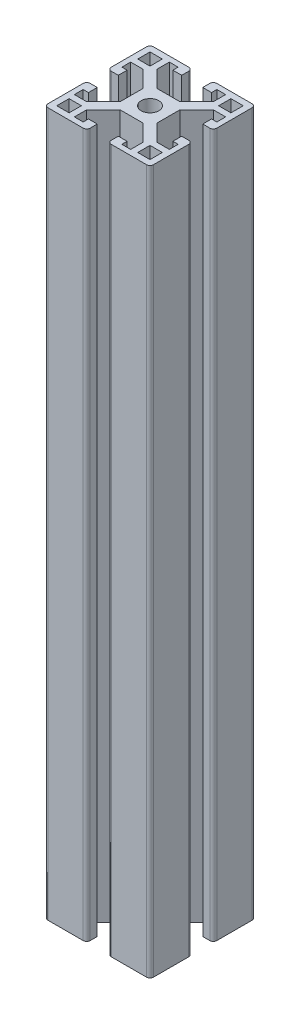
SolidWorks part; units mm, degrees
material "1060 Alloy"
ref_plane "Front Plane" through (0, 0, 0) normal (0, 0, 1) x (1, 0, 0)
ref_plane "Top Plane" through (0, 0, 0) normal (0, 1, 0) x (1, 0, 0)
ref_plane "Right Plane" through (0, 0, 0) normal (1, 0, 0) x (0, 0, -1)
sketch "Sketch1" plane through (0, 0, 0) normal (0, 1, 0) x (1, 0, 0)
  line L0 (-15, 7.5) -> (-15, -4.5)
  line L1 (-15, 7.5) -> (15, 7.5) construction
  line L2 (-15, 7.5) -> (-15, -7.5) construction
  line L3 (-15, -7.5) -> (15, -7.5) construction
  line L4 (15, 7.5) -> (15, -7.5) construction
  line L5 (0, -7.5) -> (0, 7.5) construction
  line L6 (-15, 0) -> (15, 0) construction
  line L7 (-15, 7.5) -> (-3, 7.5)
  line L8 (-15, -4.5) -> (-12, -4.5)
  line L9 (-12, -4.5) -> (-12, -2)
  line L10 (-12, -2) -> (-13.5, -2)
  line L11 (-13.5, -2) -> (-13.5, 0.5)
  line L12 (-13.5, 0.5) -> (-10, 0.5)
  line L13 (-5.25, -2.25) -> (5.25, -2.25) construction
  line L14 (-5.25, -2.25) -> (-5.25, -12.75) construction
  line L15 (-5.25, -12.75) -> (5.25, -12.75) construction
  line L16 (5.25, -2.25) -> (5.25, -12.75) construction
  line L17 (0, -12.75) -> (0, -2.25) construction
  line L18 (-5.25, -7.5) -> (5.25, -7.5) construction
  line L19 (-2.5857, -4.9143) -> (-15, 7.5) construction
  line L20 (-10, 0.5) -> (-5.25, -4.25)
  line L21 (-8, 2.5) -> (-3.25, -2.25)
  line L22 (-3, 7.5) -> (-3, 4.5)
  line L23 (-3, 4.5) -> (-5.5, 4.5)
  line L24 (-5.5, 4.5) -> (-5.5, 6)
  line L25 (-5.5, 6) -> (-8, 6)
  line L26 (-8, 6) -> (-8, 2.5)
  line L27 (5.5, 4.5) -> (5.5, 6)
  line L28 (-13.25, 5.75) -> (-9.75, 5.75)
  line L29 (-13.25, 5.75) -> (-13.25, 2.25)
  line L30 (-13.25, 2.25) -> (-9.75, 2.25)
  line L31 (-9.75, 5.75) -> (-9.75, 2.25)
  line L32 (-11.5, 2.25) -> (-11.5, 5.75) construction
  line L33 (-13.25, 4) -> (-9.75, 4) construction
  line L34 (13.25, 2.25) -> (9.75, 2.25)
  line L35 (13.25, 5.75) -> (13.25, 2.25)
  line L36 (13.25, 5.75) -> (9.75, 5.75)
  line L37 (9.75, 5.75) -> (9.75, 2.25)
  line L38 (3, 4.5) -> (5.5, 4.5)
  line L39 (3, 7.5) -> (3, 4.5)
  line L40 (5.5, 6) -> (8, 6)
  line L41 (8, 6) -> (8, 2.5)
  line L42 (15, 7.5) -> (3, 7.5)
  line L43 (13.5, 0.5) -> (10, 0.5)
  line L44 (13.5, -2) -> (13.5, 0.5)
  line L45 (12, -2) -> (13.5, -2)
  line L46 (15, 7.5) -> (15, -4.5)
  line L47 (15, -4.5) -> (12, -4.5)
  line L48 (12, -4.5) -> (12, -2)
  line L49 (8, 2.5) -> (3.25, -2.25)
  line L50 (10, 0.5) -> (5.25, -4.25)
  line L51 (-5.25, -4.25) -> (-5.25, -10.75)
  line L52 (-3.25, -2.25) -> (3.25, -2.25)
  line L53 (5.25, -4.25) -> (5.25, -10.75)
  line L54 (15, -22.5) -> (15, -10.5)
  line L55 (15, -10.5) -> (12, -10.5)
  line L56 (12, -10.5) -> (12, -13)
  line L57 (12, -13) -> (13.5, -13)
  line L58 (13.5, -13) -> (13.5, -15.5)
  line L59 (13.5, -15.5) -> (10, -15.5)
  line L60 (13.25, -17.25) -> (9.75, -17.25)
  line L61 (13.25, -20.75) -> (13.25, -17.25)
  line L62 (13.25, -20.75) -> (9.75, -20.75)
  line L63 (9.75, -20.75) -> (9.75, -17.25)
  line L64 (8, -21) -> (8, -17.5)
  line L65 (5.5, -21) -> (8, -21)
  line L66 (5.5, -19.5) -> (5.5, -21)
  line L67 (15, -22.5) -> (3, -22.5)
  line L68 (3, -22.5) -> (3, -19.5)
  line L69 (3, -19.5) -> (5.5, -19.5)
  line L70 (10, -15.5) -> (5.25, -10.75)
  line L71 (8, -17.5) -> (3.25, -12.75)
  line L72 (-3, -22.5) -> (-3, -19.5)
  line L73 (-3, -19.5) -> (-5.5, -19.5)
  line L74 (-5.5, -19.5) -> (-5.5, -21)
  line L75 (-5.5, -21) -> (-8, -21)
  line L76 (-8, -21) -> (-8, -17.5)
  line L77 (-15, -22.5) -> (-3, -22.5)
  line L78 (-9.75, -20.75) -> (-9.75, -17.25)
  line L79 (-13.25, -20.75) -> (-9.75, -20.75)
  line L80 (-13.25, -20.75) -> (-13.25, -17.25)
  line L81 (-13.25, -17.25) -> (-9.75, -17.25)
  line L82 (-13.5, -15.5) -> (-10, -15.5)
  line L83 (-13.5, -13) -> (-13.5, -15.5)
  line L84 (-12, -13) -> (-13.5, -13)
  line L85 (-15, -22.5) -> (-15, -10.5)
  line L86 (-15, -10.5) -> (-12, -10.5)
  line L87 (-12, -10.5) -> (-12, -13)
  line L88 (-3.25, -12.75) -> (3.25, -12.75)
  line L89 (-8, -17.5) -> (-3.25, -12.75)
  line L90 (-10, -15.5) -> (-5.25, -10.75)
  circle A0 centre (0, -7.5) radius 2.5
  point P0 (0, 0)
  point P18 (-11.5, 4)
  dimension "D7" = 1.5
  dimension "D19" = 5
  dimension "D1" = 30
  dimension "D2" = 15
  dimension "D3" = 12
  dimension "D4" = 12
  dimension "D5" = 3
  dimension "D6" = 2.5
  dimension "D8" = 2.5
  dimension "D9" = 10.5
  dimension "D10" = 3.5
  dimension "D11" = 45
  dimension "D12" = 3
  dimension "D13" = 2.5
  dimension "D14" = 1.5
  dimension "D15" = 2.5
  dimension "D16" = 3.5
  dimension "D17" = 3.5
  dimension "D18" = 3.5
extrude "Boss-Extrude1" add sketch "Sketch1" against normal blind 200
fillet "Fillet1" radius 1 12 edges at (-15, -100, -7.5) (-3, -100, -7.5) (3, -100, -7.5) (15, -100, -7.5) (15, -100, 4.5) (-15, -100, 4.5) (-15, -100, 10.5) (-15, -100, 22.5) (-3, -100, 22.5) (15, -100, 10.5) (3, -100, 22.5) (15, -100, 22.5)
